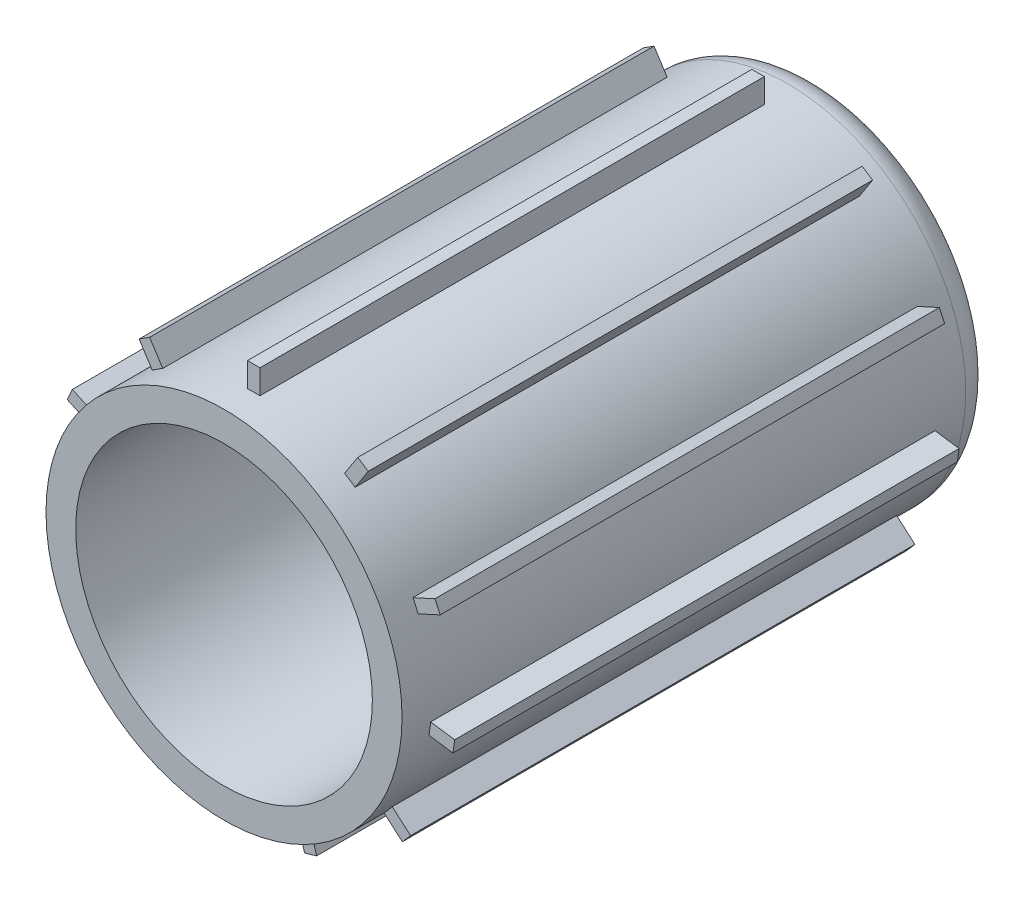
SolidWorks part; units mm, degrees
ref_plane "Front Plane" through (0, 0, 0) normal (0, 0, 1) x (1, 0, 0)
ref_plane "Top Plane" through (0, 0, 0) normal (0, 1, 0) x (1, 0, 0)
ref_plane "Right Plane" through (0, 0, 0) normal (1, 0, 0) x (0, 0, -1)
sketch "Sketch1" plane through (0, 0, 0) normal (0, 0, 1) x (1, 0, 0)
  circle A0 centre (0, 0) radius 60
  dimension "D1" = 120
extrude "Boss-Extrude1" add sketch "Sketch1" along normal blind 200
sketch "Sketch2" plane through (0, 0, 200) normal (0, 0, 1) x (1, 0, 0)
  circle A0 centre (0, 0) radius 50
  dimension "D1" = 100
extrude "Cut-Extrude1" cut sketch "Sketch2" against normal blind 180
fillet "Fillet1" radius 10 1 edges at (60, 0, 0)
sketch "Sketch3" plane through (0, 0, 20) normal (0, 0, 1) x (1, 0, 0)
  line L0 (34.009, 49.0198) -> (35.0657, 58.4625) construction
  line L1 (2.1081, 59.6247) -> (-2.1081, 59.6247)
  line L2 (2.1081, 59.6247) -> (2.1081, 68.1397)
  line L3 (2.1081, 68.1397) -> (-2.1081, 68.1397)
  line L4 (-2.1081, 59.6247) -> (-2.1081, 68.1397)
  line L5 (2.1081, 59.6247) -> (-2.1081, 68.1397) construction
  line L6 (2.1081, 68.1397) -> (-2.1081, 59.6247) construction
  line L7 (38.6125, 56.1831) -> (30.4621, 51.2992) construction
  line L8 (34.009, 49.0198) -> (38.6125, 56.1831)
  line L9 (34.009, 49.0198) -> (30.4621, 51.2992)
  line L10 (30.4621, 51.2992) -> (35.0657, 58.4625)
  line L11 (38.6125, 56.1831) -> (35.0657, 58.4625)
  line L12 (55.1123, 22.8514) -> (61.1064, 30.2238) construction
  line L13 (62.8578, 26.3887) -> (53.3608, 26.6866) construction
  line L14 (55.1123, 22.8514) -> (62.8578, 26.3887)
  line L15 (55.1123, 22.8514) -> (53.3608, 26.6866)
  line L16 (53.3608, 26.6866) -> (61.1064, 30.2238)
  line L17 (62.8578, 26.3887) -> (61.1064, 30.2238)
  line L18 (58.7178, -10.5721) -> (67.7462, -7.6107) construction
  line L19 (67.1462, -11.7839) -> (59.3178, -6.3989) construction
  line L20 (58.7178, -10.5721) -> (67.1462, -11.7839)
  line L21 (58.7178, -10.5721) -> (59.3178, -6.3989)
  line L22 (59.3178, -6.3989) -> (67.7462, -7.6107)
  line L23 (67.1462, -11.7839) -> (67.7462, -7.6107)
  line L24 (43.6809, -40.639) -> (52.8771, -43.0289) construction
  line L25 (50.1161, -46.2152) -> (46.4418, -37.4527) construction
  line L26 (43.6809, -40.639) -> (50.1161, -46.2152)
  line L27 (43.6809, -40.639) -> (46.4418, -37.4527)
  line L28 (46.4418, -37.4527) -> (52.8771, -43.0289)
  line L29 (50.1161, -46.2152) -> (52.8771, -43.0289)
  line L30 (14.7755, -57.8034) -> (21.2199, -64.7857) construction
  line L31 (17.1745, -65.9735) -> (18.8209, -56.6156) construction
  line L32 (14.7755, -57.8034) -> (17.1745, -65.9735)
  line L33 (14.7755, -57.8034) -> (18.8209, -56.6156)
  line L34 (18.8209, -56.6156) -> (21.2199, -64.7857)
  line L35 (17.1745, -65.9735) -> (21.2199, -64.7857)
  line L36 (-18.8209, -56.6156) -> (-17.1745, -65.9735) construction
  line L37 (-21.2199, -64.7857) -> (-14.7755, -57.8034) construction
  line L38 (-18.8209, -56.6156) -> (-21.2199, -64.7857)
  line L39 (-18.8209, -56.6156) -> (-14.7755, -57.8034)
  line L40 (-14.7755, -57.8034) -> (-17.1745, -65.9735)
  line L41 (-21.2199, -64.7857) -> (-17.1745, -65.9735)
  line L42 (-46.4418, -37.4527) -> (-50.1161, -46.2152) construction
  line L43 (-52.8771, -43.0289) -> (-43.6809, -40.639) construction
  line L44 (-46.4418, -37.4527) -> (-52.8771, -43.0289)
  line L45 (-46.4418, -37.4527) -> (-43.6809, -40.639)
  line L46 (-43.6809, -40.639) -> (-50.1161, -46.2152)
  line L47 (-52.8771, -43.0289) -> (-50.1161, -46.2152)
  line L48 (-59.3178, -6.3989) -> (-67.1462, -11.7839) construction
  line L49 (-67.7462, -7.6107) -> (-58.7178, -10.5721) construction
  line L50 (-59.3178, -6.3989) -> (-67.7462, -7.6107)
  line L51 (-59.3178, -6.3989) -> (-58.7178, -10.5721)
  line L52 (-58.7178, -10.5721) -> (-67.1462, -11.7839)
  line L53 (-67.7462, -7.6107) -> (-67.1462, -11.7839)
  line L54 (-53.3608, 26.6866) -> (-62.8578, 26.3887) construction
  line L55 (-61.1064, 30.2238) -> (-55.1123, 22.8514) construction
  line L56 (-53.3608, 26.6866) -> (-61.1064, 30.2238)
  line L57 (-53.3608, 26.6866) -> (-55.1123, 22.8514)
  line L58 (-55.1123, 22.8514) -> (-62.8578, 26.3887)
  line L59 (-61.1064, 30.2238) -> (-62.8578, 26.3887)
  line L60 (-30.4621, 51.2992) -> (-38.6125, 56.1831) construction
  line L61 (-35.0657, 58.4625) -> (-34.009, 49.0198) construction
  line L62 (-30.4621, 51.2992) -> (-35.0657, 58.4625)
  line L63 (-30.4621, 51.2992) -> (-34.009, 49.0198)
  line L64 (-34.009, 49.0198) -> (-38.6125, 56.1831)
  line L65 (-35.0657, 58.4625) -> (-38.6125, 56.1831)
  point P0 (0, 63.8822)
  point P8 (34.5373, 53.7411)
  point P13 (58.1093, 26.5376)
  point P18 (63.232, -9.0914)
  point P23 (48.279, -41.834)
  point P28 (17.9977, -61.2945)
  point P33 (-17.9977, -61.2945)
  point P38 (-48.279, -41.834)
  point P43 (-63.232, -9.0914)
  point P48 (-58.1093, 26.5376)
  point P53 (-34.5373, 53.7411)
  point P58 (0, 0)
  dimension "D1" = 11
extrude "Boss-Extrude2" add sketch "Sketch3" along normal blind 170
sketch "Sketch4" plane through (0, 0, 0) normal (0, 0, -1) x (-1, 0, 0)
  circle A0 centre (0, 0) radius 20
  dimension "D1" = 40
extrude "Cut-Extrude3" cut sketch "Sketch4" against normal blind 25
